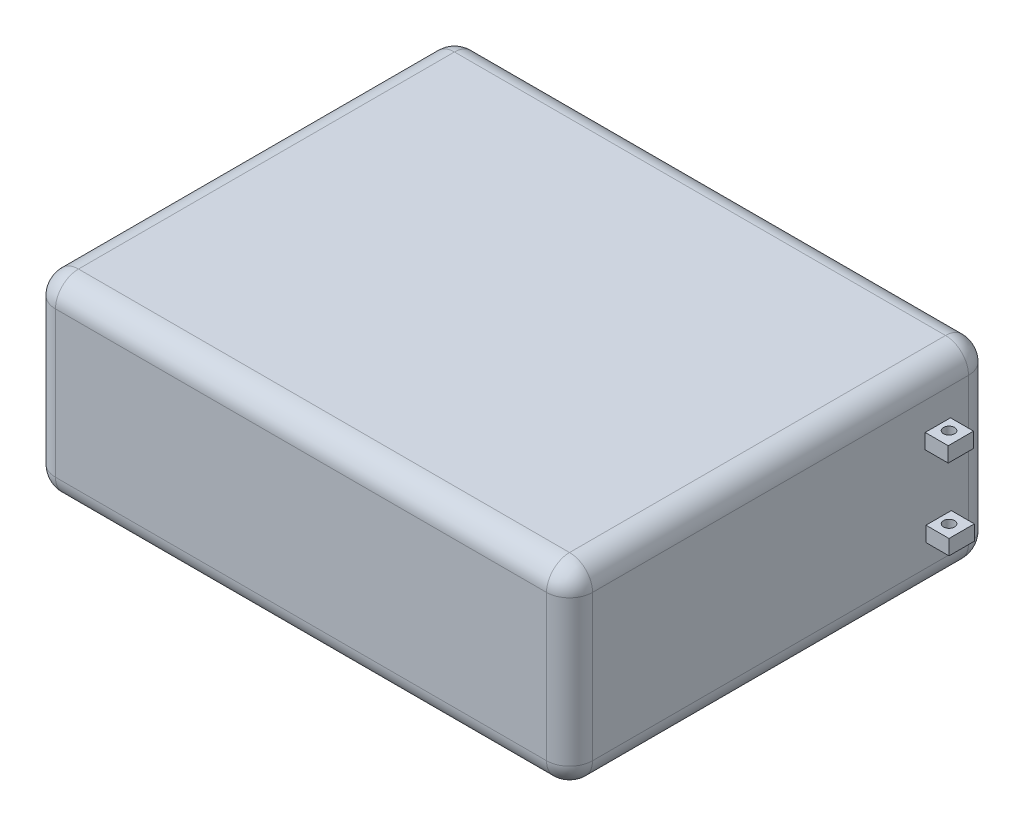
SolidWorks part; units mm, degrees
ref_plane "Front Plane" through (0, 0, 0) normal (0, 0, 1) x (1, 0, 0)
ref_plane "Top Plane" through (0, 0, 0) normal (0, 1, 0) x (1, 0, 0)
ref_plane "Right Plane" through (0, 0, 0) normal (1, 0, 0) x (0, 0, -1)
sketch "Sketch1" plane through (0, 0, 0) normal (0, 1, 0) x (1, 0, 0)
  line L1 (-35, 27.5) -> (35, 27.5)
  line L2 (-35, 27.5) -> (-35, -27.5)
  line L3 (-35, -27.5) -> (35, -27.5)
  line L4 (35, 27.5) -> (35, -27.5)
  line L5 (-35, 27.5) -> (35, -27.5) construction
  line L6 (-35, -27.5) -> (35, 27.5) construction
  point P0 (0, 0)
  dimension "D1" = 70
  dimension "D2" = 55
extrude "Boss-Extrude1" add sketch "Sketch1" along normal blind 25
fillet "Fillet1" radius 3 12 edges at (0, 25, 27.5) (35, 12.5, 27.5) (35, 25, 0) (35, 12.5, -27.5) (0, 25, -27.5) (-35, 12.5, -27.5) (-35, 25, 0) (-35, 12.5, 27.5) (0, 0, -27.5) (-35, 0, 0) (0, 0, 27.5) (35, 0, 0)
sketch "Sketch2" plane through (35, 0, 0) normal (1, 0, 0) x (0, 0, -1)
  line L1 (18.8514, 18.3798) -> (22.1523, 18.3798)
  line L2 (18.8514, 18.3798) -> (18.8514, 16.4198)
  line L3 (18.8514, 16.4198) -> (22.1523, 16.4198)
  line L4 (22.1523, 18.3798) -> (22.1523, 16.4198)
  line L5 (18.8514, 18.3798) -> (22.1523, 16.4198) construction
  line L6 (18.8514, 16.4198) -> (22.1523, 18.3798) construction
  line L7 (18.9545, 7.8581) -> (22.2555, 7.8581)
  line L8 (18.9545, 7.8581) -> (18.9545, 5.8981)
  line L9 (18.9545, 5.8981) -> (22.2555, 5.8981)
  line L10 (22.2555, 7.8581) -> (22.2555, 5.8981)
  line L11 (18.9545, 7.8581) -> (22.2555, 5.8981) construction
  line L12 (18.9545, 5.8981) -> (22.2555, 7.8581) construction
  point P0 (20.5018, 17.3998)
  point P5 (20.605, 6.8781)
  point P10 (20.5018, 17.3998)
extrude "Boss-Extrude2" add sketch "Sketch2" along normal blind 3
sketch "Sketch3" plane through (0, 18.3798, 0) normal (0, 1, 0) x (1, 0, 0)
  circle A0 centre (36.3458, 20.6134) radius 0.7196
extrude "Cut-Extrude1" cut sketch "Sketch3" against normal blind 22
